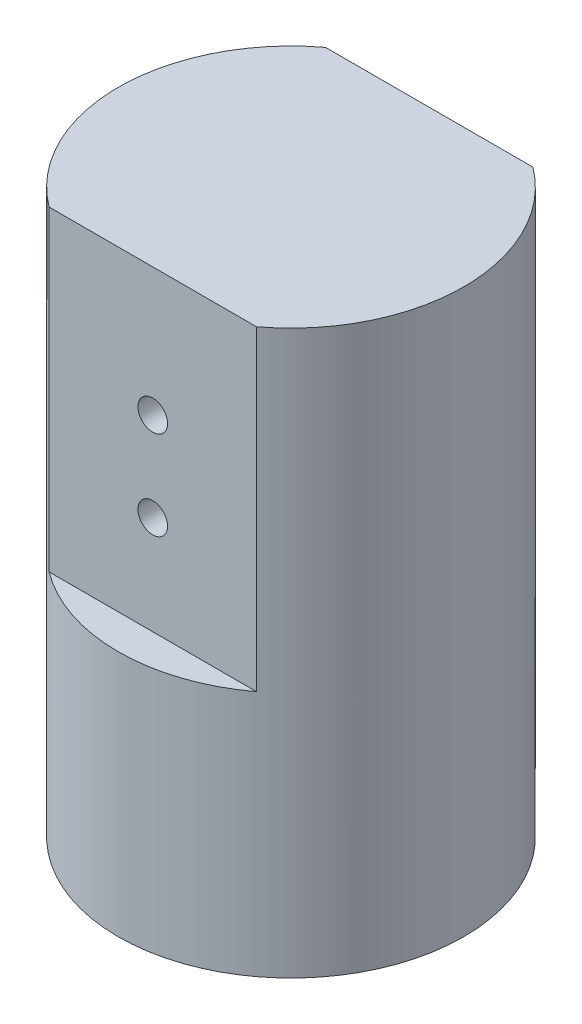
SolidWorks part; units mm, degrees
ref_plane "Front Plane" through (0, 0, 0) normal (0, 0, 1) x (1, 0, 0)
ref_plane "Top Plane" through (0, 0, 0) normal (0, 1, 0) x (1, 0, 0)
ref_plane "Right Plane" through (0, 0, 0) normal (1, 0, 0) x (0, 0, -1)
sketch "Sketch1" plane through (0, 0, 0) normal (0, 1, 0) x (1, 0, 0)
  circle A0 centre (0, 0) radius 22.225
  dimension "D1" = 44.45
extrude "Boss-Extrude1" add sketch "Sketch1" along normal blind 91.44
ref_plane "Plane1" through (22.225, 0, 0) normal (1, 0, 0) x (0, 0, -1)
sketch "Sketch2" plane through (22.225, 0, 0) normal (1, 0, 0) x (0, 0, -1)
  line L0 (22.225, 91.44) -> (-22.225, 91.44) construction
  line L1 (-17.78, 91.44) -> (-22.225, 91.44)
  line L2 (-17.78, 91.44) -> (-17.78, 50.8)
  line L3 (-17.78, 50.8) -> (-22.225, 50.8)
  line L4 (-22.225, 91.44) -> (-22.225, 50.8)
  line L5 (22.225, 0) -> (22.225, 91.44) construction
  line L6 (17.78, 91.44) -> (22.225, 91.44)
  line L7 (17.78, 91.44) -> (17.78, 50.8)
  line L8 (17.78, 50.8) -> (22.225, 50.8)
  line L9 (22.225, 91.44) -> (22.225, 50.8)
  line L10 (-22.225, 91.44) -> (-22.225, 0) construction
  line L11 (-17.78, 50.8) -> (-20.955, 50.8) construction
  line L12 (-17.78, 104.55) -> (-17.78, 50.8) construction
extrude "Cut-Extrude1" cut sketch "Sketch2" against normal up to next
sketch "Sketch4" plane through (0, 0, 17.78) normal (0, 0, 1) x (1, 0, 0)
  line L0 (0, 91.44) -> (0, 50.8) construction
  line L1 (-13.335, 91.44) -> (13.335, 91.44) construction
  line L2 (13.335, 50.8) -> (-13.335, 50.8) construction
  circle A0 centre (0, 74.93) radius 1.905
  circle A1 centre (0, 63.5) radius 1.905
  dimension "D3" = 3.81
  dimension "D1" = 12.7
  dimension "D2" = 11.43
extrude "Cut-Extrude2" cut sketch "Sketch4" against normal through all
sketch "Sketch6" plane through (-69.7934, -6.35, 649.2198) normal (1, 0, 0) x (0, 0, -1)
  line L0 (675.2548, 25.4) -> (623.1848, 25.4) construction
  line L1 (626.9948, 6.35) -> (671.4448, 6.35)
  line L2 (626.9948, 6.35) -> (626.9948, 25.4)
  line L3 (626.9948, 25.4) -> (671.4448, 25.4)
  line L4 (671.4448, 6.35) -> (671.4448, 25.4)
extrude "Cut-Extrude3" cut sketch "Sketch6" along normal through all
